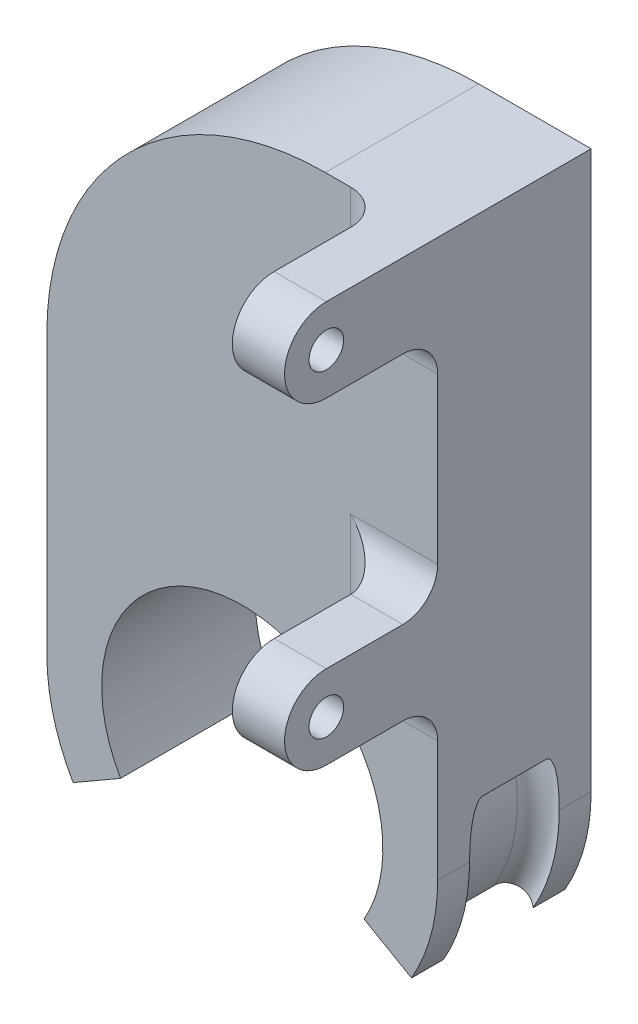
SolidWorks part; units mm, degrees
ref_plane "Front Plane" through (0, 0, 0) normal (0, 0, 1) x (1, 0, 0)
ref_plane "Top Plane" through (0, 0, 0) normal (0, 1, 0) x (1, 0, 0)
ref_plane "Right Plane" through (0, 0, 0) normal (1, 0, 0) x (0, 0, -1)
sketch "Sketch1" plane through (0, 0, 0) normal (0, 0, 1) x (1, 0, 0)
  line L0 (-17.827, 50.8) -> (17.827, 50.8)
  line L3 (-17.827, 50.8) -> (-17.827, 0)
  line L5 (0, 0) -> (0, 50.8) construction
  line L7 (17.827, 50.8) -> (17.827, 0)
  line L8 (-11.1085, -6.4135) -> (0, 0) construction
  line L9 (0, 0) -> (11.1085, -6.4135) construction
  line L10 (-11.1085, -6.4135) -> (11.1085, -6.4135) construction
  line L11 (-11.1085, -6.4135) -> (-15.4386, -8.9135)
  line L12 (11.1085, -6.4135) -> (15.4386, -8.9135)
  arc A1 (-11.1085, -6.4135) -> (11.1085, -6.4135) centre (0, 0) cw
  arc A2 (-15.4386, -8.9135) -> (-17.827, 0) centre (0, 0) cw
  arc A3 (15.4386, -8.9135) -> (17.827, 0) centre (0, 0) ccw
  point P5 (17.827, 3.2174)
  dimension "D4" = 12.827
  dimension "D7" = 50.8
  dimension "D5" = 120
  dimension "D6" = 5
extrude "Boss-Extrude2" add sketch "Sketch1" along normal mid plane 14
sketch "Croquis1" plane through (0, 0, 0) normal (1, 0, 0) x (0, 0, -1)
  line L0 (-2.8575, 16.8275) -> (2.8575, 16.8275) construction
  line L1 (-2.8575, 18.415) -> (2.8575, 18.415)
  line L2 (-2.8575, 15.24) -> (2.8575, 15.24)
  line L4 (0, 0) -> (-7, 0) construction
  line L6 (0, 0) -> (0, 15.24) construction
  arc A0 (-2.8575, 18.415) -> (-2.8575, 15.24) centre (-2.8575, 16.8275) ccw
  arc A1 (2.8575, 15.24) -> (2.8575, 18.415) centre (2.8575, 16.8275) ccw
  point P2 (0, 16.8275)
  dimension "D1" = 8.89
  dimension "D2" = 1.5875
  dimension "D3" = 15.24
revolve "Cortar-Revolución1" cut sketch "Croquis1" angle 270 mid plane about L4
sketch "Croquis3" plane through (17.827, 0, 0) normal (1, 0, 0) x (0, 0, -1)
  line L0 (-7, 32.49) -> (-17.16, 32.49) construction
  line L1 (-7, 50.8) -> (-7, 0) construction
  line L2 (-7, 50.8) -> (7, 50.8) construction
  line L3 (-17.16, 50.8) -> (-7, 50.8)
  line L4 (-17.16, 43.18) -> (-7, 43.18)
  line L5 (-7, 43.18) -> (-7, 50.8)
  line L6 (-7, 21.8) -> (-7, 14.18)
  line L7 (-17.16, 21.8) -> (-7, 21.8)
  line L8 (-17.16, 14.18) -> (-7, 14.18)
  circle A0 centre (-17.16, 46.99) radius 1.575
  circle A1 centre (-17.16, 46.99) radius 3.81
  circle A2 centre (-17.16, 17.99) radius 3.81
  circle A3 centre (-17.16, 17.99) radius 1.575
  line M8 (-7, 50.8) -> (-7, 0)
  dimension "D1" = 29
  dimension "D2" = 3.15
  dimension "D3" = 10.16
  dimension "D4" = 7.62
extrude "Saliente-Extruir2" add sketch "Croquis3" against normal blind 4.7625 contours L7 A2 L8 M8 | A2 A3 | A1 L4 L3 M8 | A1 A0
fillet "Redondeo3" radius 3.175 5 edges at (13.0645, 46.99, 7) (15.4457, 43.18, 7) (15.4457, 14.18, 7) (15.4457, 21.8, 7) (13.0645, 17.99, 7)
fillet "Redondeo4" radius 25.4 1 edges at (-17.827, 50.8, 0)
